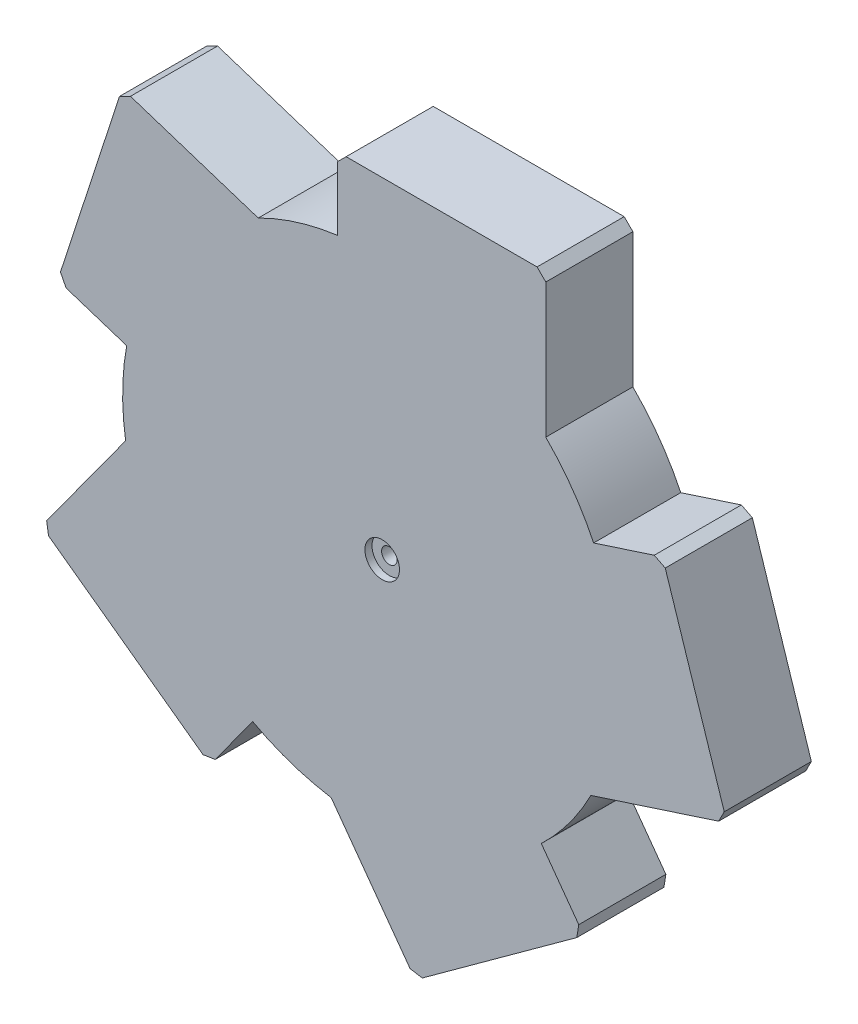
SolidWorks part; units mm, degrees
ref_plane "Front" through (0, 0, 0) normal (0, 0, 1) x (1, 0, 0)
ref_plane "Top" through (0, 0, 0) normal (0, 1, 0) x (1, 0, 0)
ref_plane "Right" through (0, 0, 0) normal (1, 0, 0) x (0, 0, -1)
sketch "Sketch1" plane through (0, 0, 0) normal (0, 0, 1) x (1, 0, 0)
  line L0 (-2.7803, 36.497) -> (-3.7803, 35.497)
  line L2 (20.1387, 20.0719) -> (20.1387, 35.497)
  line L3 (19.1387, 36.497) -> (-2.7803, 36.497)
  line L4 (-3.7803, 28.1808) -> (-3.7803, 35.497)
  line L5 (-3.3718, 35.9055) -> (-3.7803, 36.497) construction
  line L6 (20.1387, 36.497) -> (19.7302, 35.9055) construction
  line L7 (20.1387, 35.497) -> (19.1387, 36.497)
  line L8 (33.8516, 13.9224) -> (32.5915, 14.5645)
  line L9 (25.3127, -12.9504) -> (39.9829, -8.1838)
  line L10 (40.6249, -6.9237) -> (33.8516, 13.9224)
  line L11 (25.6334, 12.3036) -> (32.5915, 14.5645)
  line L12 (39.9829, -8.1838) -> (40.6249, -6.9237)
  line L13 (33.1062, 14.3022) -> (33.5426, 14.8735) construction
  line L14 (40.9339, -7.8748) -> (40.2451, -7.6691) construction
  line L15 (23.7017, -27.8925) -> (23.9229, -26.4957)
  line L16 (-4.4945, -28.0757) -> (4.5721, -40.5549)
  line L17 (5.9689, -40.7761) -> (23.7017, -27.8925)
  line L18 (19.6226, -20.5767) -> (23.9229, -26.4957)
  line L19 (4.5721, -40.5549) -> (5.9689, -40.7761)
  line L20 (23.8326, -27.0662) -> (24.5107, -27.3047) construction
  line L21 (5.1599, -41.3639) -> (5.1426, -40.6453) construction
  line L22 (-19.2031, -31.1609) -> (-17.8063, -30.9397)
  line L23 (-28.0905, -4.4013) -> (-37.1571, -16.8805)
  line L24 (-36.9359, -18.2773) -> (-19.2031, -31.1609)
  line L25 (-13.5059, -25.0207) -> (-17.8063, -30.9397)
  line L26 (-37.1571, -16.8805) -> (-36.9359, -18.2773)
  line L27 (-18.1571, -21.8808) -> (-18.3941, -31.7487) construction
  line L28 (-37.7449, -17.6895) -> (-37.0668, -17.451) construction
  line L29 (-35.5699, 8.634) -> (-34.9279, 7.3739)
  line L30 (-12.8663, 25.3556) -> (-27.5365, 30.1222)
  line L31 (-28.7966, 29.4801) -> (-35.5699, 8.634)
  line L32 (-27.9697, 5.1131) -> (-34.9279, 7.3739)
  line L33 (-27.5365, 30.1222) -> (-28.7966, 29.4801)
  line L34 (-26.4207, 10.5069) -> (-35.8789, 7.6829) construction
  line L35 (-28.4875, 30.4312) -> (-28.0512, 29.8599) construction
  arc A0 (-27.9697, 5.1131) -> (-28.0905, -4.4013) centre (0, 0) ccw
  arc A1 (-27.9697, 5.1131) -> (-28.0905, -4.4013) centre (0, 0) ccw
  arc A2 (-27.9697, 5.1131) -> (-28.0905, -4.4013) centre (0, 0) ccw
  arc A3 (-27.9697, 5.1131) -> (-28.0905, -4.4013) centre (0, 0) ccw
  arc A4 (-27.9697, 5.1131) -> (-28.0905, -4.4013) centre (0, 0) ccw
  arc A5 (-13.5059, -25.0207) -> (-4.4945, -28.0757) centre (0, 0) ccw
  arc A6 (-13.5059, -25.0207) -> (-4.4945, -28.0757) centre (0, 0) ccw
  arc A7 (-13.5059, -25.0207) -> (-4.4945, -28.0757) centre (0, 0) ccw
  arc A8 (-13.5059, -25.0207) -> (-4.4945, -28.0757) centre (0, 0) ccw
  arc A9 (-13.5059, -25.0207) -> (-4.4945, -28.0757) centre (0, 0) ccw
  arc A10 (19.6226, -20.5767) -> (25.3127, -12.9504) centre (0, 0) ccw
  arc A11 (19.6226, -20.5767) -> (25.3127, -12.9504) centre (0, 0) ccw
  arc A12 (19.6226, -20.5767) -> (25.3127, -12.9504) centre (0, 0) ccw
  arc A13 (19.6226, -20.5767) -> (25.3127, -12.9504) centre (0, 0) ccw
  arc A14 (19.6226, -20.5767) -> (25.3127, -12.9504) centre (0, 0) ccw
  arc A15 (25.6334, 12.3036) -> (20.1387, 20.0719) centre (0, 0) ccw
  arc A16 (25.6334, 12.3036) -> (20.1387, 20.0719) centre (0, 0) ccw
  arc A17 (25.6334, 12.3036) -> (20.1387, 20.0719) centre (0, 0) ccw
  arc A18 (25.6334, 12.3036) -> (20.1387, 20.0719) centre (0, 0) ccw
  arc A19 (25.6334, 12.3036) -> (20.1387, 20.0719) centre (0, 0) ccw
  arc A20 (-3.7803, 28.1808) -> (-12.8663, 25.3556) centre (0, 0) ccw
  arc A21 (-3.7803, 28.1808) -> (-12.8663, 25.3556) centre (0, 0) ccw
  arc A22 (-3.7803, 28.1808) -> (-12.8663, 25.3556) centre (0, 0) ccw
  arc A23 (-3.7803, 28.1808) -> (-12.8663, 25.3556) centre (0, 0) ccw
  arc A24 (-3.7803, 28.1808) -> (-12.8663, 25.3556) centre (0, 0) ccw
  point P3 (8.1792, 19.1764)
extrude "Boss-Extrude1" add sketch "Sketch1" along normal blind 10 contours L4 A20 L30 L33 L31 L29 L32 A0 L23 L26 L24 L22 L25 A5 L16 L19 L17 L15 L18 A10 L9 L12 L10 L8 L11 A15 L2 L7 L3 L0
hole_wizard "CBORE for #0 Binding Head Machine Screw1" positions "Sketch4" profile "Sketch5" counterbore size "#0" standard "ANSI Inch" end condition through all
sketch "Sketch4" plane through (0, 0, 10) normal (0, 0, 1) x (1, 0, 0)
  point P0 (1.3632, -1.4942)
  point P2 (1.3632, -1.4942)
sketch "Sketch5" plane through (1.3632, -1.4942, 10) normal (1, 0, 0) x (0, -1, 0)
  line L0 (0, 0) -> (0, 10)
  line L1 (0, 10) -> (0.889, 10)
  line L3 (0.889, 10) -> (0.889, 0.8128)
  line L4 (0.889, 0.8128) -> (1.985, 0.8128)
  line L5 (1.985, 0.8128) -> (1.985, 0)
  line L7 (1.985, 0) -> (0, 0)
  line L11 (0, -6.35) -> (0, 107.95) construction
  dimension "Thru Hole Dia." = 1.778
  dimension "Thru Hole Depth" = 10
  dimension "C'Bore Dia." = 3.97
  dimension "C'Bore Depth" = 0.8128
scale "Scale1" scale about centroid uniform scaling yes scale factor 0.5
sketch "Sketch6" plane through (0, 0, 2.4995) normal (0, 0, -1) x (-1, 0, 0)
  circle A1 centre (-0.681, -0.7464) radius 0.4445
extrude "Boss-Extrude2" add sketch "Sketch6" along normal blind 2 separate body
